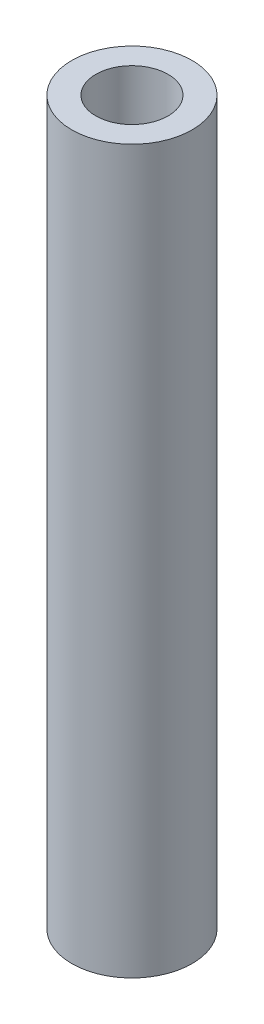
SolidWorks part; units mm, degrees
ref_plane "Front Plane" through (0, 0, 0) normal (0, 0, 1) x (1, 0, 0)
ref_plane "Top Plane" through (0, 0, 0) normal (0, 1, 0) x (1, 0, 0)
ref_plane "Right Plane" through (0, 0, 0) normal (1, 0, 0) x (0, 0, -1)
sketch "Sketch1" plane through (0, 0, 0) normal (0, 1, 0) x (1, 0, 0)
  circle A0 centre (0, 0) radius 2.5
  circle A1 centre (0, 0) radius 1.5
  dimension "D1" = 3
  dimension "D2" = 5
extrude "Boss-Extrude1" add sketch "Sketch1" along normal blind 30
